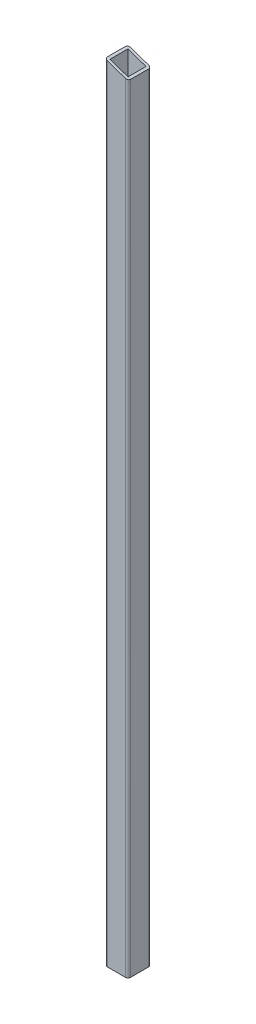
SolidWorks part; units mm, degrees
ref_plane "Front Plane" through (0, 0, 0) normal (0, 0, 1) x (1, 0, 0)
ref_plane "Top Plane" through (0, 0, 0) normal (0, 1, 0) x (1, 0, 0)
ref_plane "Right Plane" through (0, 0, 0) normal (1, 0, 0) x (0, 0, -1)
sketch "Sketch1" plane through (0, 0, 0) normal (0, 1, 0) x (1, 0, 0)
  line L1 (2.8, 0) -> (22.8, 0)
  line L2 (0, -2.8) -> (0, -22.8)
  line L3 (2.8, -25.6) -> (22.8, -25.6)
  line L4 (25.6, -2.8) -> (25.6, -22.8)
  arc A0 (22.8, 0) -> (25.6, -2.8) centre (22.8, -2.8) cw
  arc A1 (22.8, -25.6) -> (25.6, -22.8) centre (22.8, -22.8) ccw
  arc A2 (0, -22.8) -> (2.8, -25.6) centre (2.8, -22.8) ccw
  arc A3 (2.8, 0) -> (0, -2.8) centre (2.8, -2.8) ccw
  point P7 (25.6, 0)
  point P10 (25.6, -25.6)
  point P15 (0, 0)
  dimension "D2" = 2.8
  dimension "D1" = 25.6
extrude "Boss-Extrude1" add sketch "Sketch1" along normal blind 870
sketch "Sketch3" plane through (0, 0, 0) normal (0, -1, 0) x (-1, 0, 0)
  line L4 (-2.8, -2.8) -> (-22.8, -2.8)
  line L5 (-2.8, -2.8) -> (-2.8, -22.8)
  line L6 (-2.8, -22.8) -> (-22.8, -22.8)
  line L7 (-22.8, -2.8) -> (-22.8, -22.8)
  line L8 (-2.8, -2.8) -> (-22.8, -22.8) construction
  line L9 (-2.8, -22.8) -> (-22.8, -2.8) construction
  point P6 (-12.8, -12.8)
extrude "Cut-Extrude1" cut sketch "Sketch3" against normal blind 1040.5
ref_plane "Plane1" through (0, 0, 22.8) normal (0, 0, -1) x (-1, 0, 0)
sketch "Sketch4" plane through (0, 0, 22.8) normal (0, 0, -1) x (-1, 0, 0)
  line L0 (0, 870) -> (-25.6, 861.1852)
  line L1 (-25.6, 870) -> (-25.6, 0) construction
extrude "Cut-Extrude6" cut sketch "Sketch4" against normal through all and the other way through all flip side to cut
